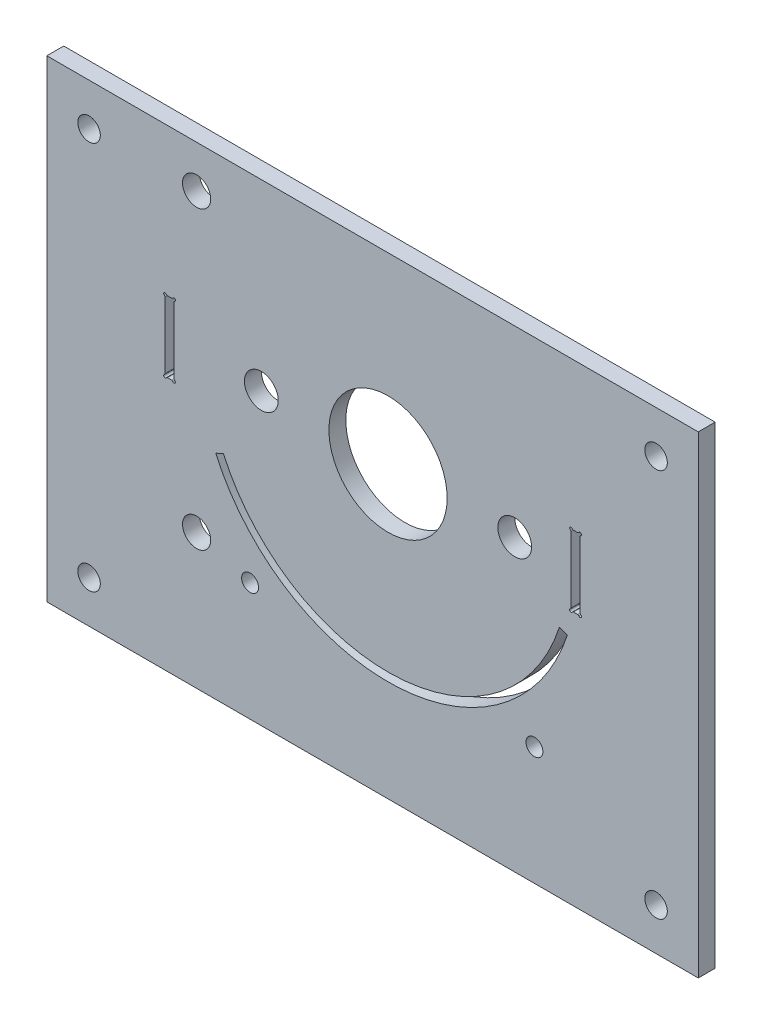
SolidWorks part; units mm, degrees
ref_plane "Front Plane" through (0, 0, 0) normal (0, 0, 1) x (1, 0, 0)
ref_plane "Top Plane" through (0, 0, 0) normal (0, 1, 0) x (1, 0, 0)
ref_plane "Right Plane" through (0, 0, 0) normal (1, 0, 0) x (0, 0, -1)
sketch "Sketch2" plane through (0, 0, 0) normal (0, 0, 1) x (1, 0, 0)
  line L12 (0, 0) -> (0, -103) construction
  line L13 (0, 50) -> (-68, 50) construction
  line L23 (0, 0) -> (0, 50) construction
  line L24 (0, 0) -> (-76, 0) construction
  line L25 (-76, -12.6) -> (-76, 12.6)
  line L26 (-76, 12.6) -> (-79.2, 12.6)
  line L27 (-79.2, 12.6) -> (-79.2, -12.6)
  line L28 (-79.2, -12.6) -> (-76, -12.6)
  line L29 (-68, 50) -> (-68, 65) construction
  line L30 (-79.2, 0) -> (-106.2, 0) construction
  line L31 (-106.2, 0) -> (-106.2, 50) construction
  line L33 (-68, 65) -> (95.2, 65)
  line L41 (0, 0) -> (60, 0) construction
  line L42 (60, 0) -> (65, 0) construction
  line L43 (65, -12.6) -> (65, 12.6)
  line L44 (65, 12.6) -> (68.2, 12.6)
  line L45 (68.2, 12.6) -> (68.2, -12.6)
  line L46 (65, -12.6) -> (68.2, -12.6)
  line L47 (68.2, 0) -> (95.2, 0) construction
  line L48 (95.2, 0) -> (95.2, 50) construction
  line L54 (-68, 50) -> (-68, -55) construction
  line L59 (95.2, 65) -> (110.2, 65)
  line L62 (0, -103) -> (110.2, -103)
  line L63 (110.2, 65) -> (110.2, -103)
  line L64 (-68, 65) -> (-106.2, 65)
  line L65 (-106.2, 65) -> (-121.2, 65)
  line L66 (-121.2, 65) -> (-121.2, -103)
  line L67 (0, -103) -> (-121.2, -103)
  circle A7 centre (0, 0) radius 21
  circle A8 centre (-68, 50) radius 5 construction
  circle A9 centre (-68, -55) radius 5 construction
  point P9 (-76, 0)
  point P13 (0, -103)
  point P25 (65, 0)
  dimension "D1" = 42
  dimension "D4" = 10
  dimension "D10" = 27
  dimension "D11" = 15
  dimension "D12" = 15
  dimension "D26" = 10
  dimension "D2" = 103
  dimension "D3" = 68
  dimension "D5" = 76
  dimension "D6" = 50
  dimension "D7" = 25.2
  dimension "D8" = 3.2
  dimension "D9" = 15
  dimension "D14" = 60
  dimension "D15" = 5
  dimension "D16" = 25.2
  dimension "D17" = 3.2
  dimension "D18" = 27
  dimension "D19" = 50
  dimension "D20" = 50
  dimension "D25" = 105
extrude "Boss-Extrude1" add sketch "Sketch2" along normal mid plane 6
sketch "Sketch6" plane through (0, 0, 0) normal (0, 0, 1) x (1, 0, 0)
  line L0 (-121.2, 65) -> (-106.2, 65) construction
  line L1 (110.2, 65) -> (-121.2, 65) construction
  line L2 (-106.2, 65) -> (-106.2, 50) construction
  line L3 (110.2, 65) -> (95.2, 65) construction
  line L4 (95.2, 65) -> (95.2, 50) construction
  line L5 (110.2, -103) -> (95.2, -103) construction
  line L6 (-121.2, -103) -> (110.2, -103) construction
  line L7 (95.2, -103) -> (95.2, -88) construction
  line L8 (-121.2, -103) -> (-106.2, -103) construction
  line L9 (-106.2, -103) -> (-106.2, -88) construction
  line L10 (-106.2, 50) -> (-68, 50) construction
  line L11 (-121.2, 65) -> (-121.2, -103) construction
  line L12 (-68, 50) -> (-68, -55) construction
  dimension "D1" = 15
  dimension "D2" = 15
  dimension "D3" = 15
  dimension "D4" = 15
  dimension "D5" = 15
  dimension "D6" = 15
  dimension "D7" = 15
  dimension "D8" = 15
  dimension "D9" = 53.2
  dimension "D10" = 105
hole_wizard "Ø10.0 (10) Diameter Hole1" positions "Sketch11" profile "Sketch12" hole size "Ø10.0" standard "AS" end condition through all
sketch "Sketch11" plane through (0, 0, 3) normal (0, 0, 1) x (1, 0, 0)
  point P0 (-68, 50)
  point P3 (-68, -55)
sketch "Sketch12" plane through (-68, 50, 3) normal (1, 0, 0) x (0, -1, 0)
  line L0 (0, 0) -> (0, 6)
  line L1 (0, 6) -> (5, 6)
  line L2 (5, 6) -> (5, 0)
  line L5 (5, 0) -> (0, 0)
  line L11 (0, -6.35) -> (0, 107.95) construction
  dimension "Thru Hole Dia." = 10
  dimension "Thru Hole Depth" = 6
hole_wizard "Ø8.0 (8) Diameter Hole1" positions "Sketch13" profile "Sketch14" hole size "Ø8.0" standard "ANSI Metric" end condition through all
sketch "Sketch13" plane through (0, 0, 3) normal (0, 0, 1) x (1, 0, 0)
  point P0 (-106.2, 50)
  point P3 (-106.2, -88)
  point P6 (95.2, -88)
  point P9 (95.2, 50)
sketch "Sketch14" plane through (-106.2, 50, 3) normal (1, 0, 0) x (0, -1, 0)
  line L0 (0, 0) -> (0, 6)
  line L1 (0, 6) -> (4, 6)
  line L2 (4, 6) -> (4, 0)
  line L5 (4, 0) -> (0, 0)
  line L11 (0, -6.35) -> (0, 107.95) construction
  dimension "Thru Hole Dia." = 8
  dimension "Thru Hole Depth" = 6
sketch "Sketch15" plane through (0, 0, 3) normal (0, 0, 1) x (1, 0, 0)
  line L0 (-45, 0) -> (45, 0) construction
  point P5 (0, 0)
  point P7 (-45, 0)
  point P8 (45, 0)
  dimension "D1" = 90
hole_wizard "Ø12.0 (12) Diameter Hole1" positions "Sketch16" profile "Sketch17" hole size "Ø12.0" standard "AS" end condition through all
sketch "Sketch16" plane through (0, 0, 3) normal (0, 0, 1) x (1, 0, 0)
  point P0 (-45, 0)
  point P3 (45, 0)
sketch "Sketch17" plane through (-45, 0, 3) normal (1, 0, 0) x (0, -1, 0)
  line L0 (0, 0) -> (0, 6)
  line L1 (0, 6) -> (6, 6)
  line L2 (6, 6) -> (6, 0)
  line L5 (6, 0) -> (0, 0)
  line L11 (0, -6.35) -> (0, 107.95) construction
  dimension "Thru Hole Dia." = 12
  dimension "Thru Hole Depth" = 6
sketch "Sketch18" plane through (0, 0, -3) normal (0, 0, -1) x (-1, 0, 0)
  line L0 (0, 0) -> (0, -67) construction
  line L1 (-60.8676, -19.7771) -> (-63.7208, -20.7041)
  line L2 (58.4669, -26.0311) -> (61.2075, -27.2514)
  line L3 (79.2, 12.6) -> (79.2, -12.6) construction
  line L4 (79.2, -12.6) -> (76, -12.6) construction
  line L5 (76, 12.6) -> (79.2, 12.6) construction
  arc A0 (-63.7208, -20.7041) -> (61.2075, -27.2514) centre (0, 0) ccw
  arc A1 (-60.8676, -19.7771) -> (58.4669, -26.0311) centre (0, 0) ccw
  dimension "D1" = 134
  dimension "D2" = 3
  dimension "D6" = 79.2
  dimension "D3" = 72
  dimension "D4" = 66
  dimension "D5" = 17.9925
  dimension "D7" = 142.9208
  dimension "D8" = 12.6
extrude "Cut-Extrude1" cut sketch "Sketch18" against normal through all both and the other way through all
sketch "Sketch19" plane through (0, 0, -3) normal (0, 0, -1) x (-1, 0, 0)
  circle A0 centre (-65, -12.6) radius 0.5
  circle A1 centre (-68.2, -12.6) radius 0.5
  circle A2 centre (-68.2, 12.6) radius 0.5
  circle A3 centre (-65, 12.6) radius 0.5
  circle A4 centre (79.2, -12.6) radius 0.5
  circle A5 centre (76, -12.6) radius 0.5
  circle A6 centre (79.2, 12.6) radius 0.5
  circle A7 centre (76, 12.6) radius 0.5
  dimension "D1" = 1
extrude "Cut-Extrude2" cut sketch "Sketch19" against normal through all
fillet "Fillet1" radius 0.5 16 edges at (-79.2, -12.1, 0) (-78.7, -12.6, 0) (-76.5, -12.6, 0) (-76, -12.1, 0) (-76, 12.1, 0) (-76.5, 12.6, 0) (-78.7, 12.6, 0) (-79.2, 12.1, 0) (65.5, -12.6, 0) (67.7, -12.6, 0) (68.2, -12.1, 0) (65, -12.1, 0) (65, 12.1, 0) (65.5, 12.6, 0) (68.2, 12.1, 0) (67.7, 12.6, 0)
sketch "Sketch20" plane through (0, 0, 3) normal (0, 0, 1) x (1, 0, 0)
  line L0 (0, 0) -> (-49, -61) construction
  line L1 (0, 0) -> (52, -61) construction
  line L2 (0, 0) -> (0, -143.0041) construction
  line L4 (-79.2, 11.734) -> (-79.2, -11.734) construction
  line L5 (67.334, 12.6) -> (65.866, 12.6) construction
  circle A1 centre (0, 0) radius 21 construction
  dimension "D1" = 42
  dimension "D2" = 38.774
  dimension "D3" = 40.446
  dimension "D4" = 61
  dimension "D5" = 61
  dimension "D6" = 79.2
  dimension "D7" = 146.534
  dimension "D8" = 0.866
  dimension "D9" = 12.6
hole_wizard "Ø6.0 (6) Diameter Hole1" positions "Sketch23" profile "Sketch22" hole size "Ø6.0" standard "AS" end condition through all
sketch "Sketch23" plane through (0, 0, 3) normal (0, 0, 1) x (1, 0, 0)
  point P0 (-49, -61)
  point P3 (52, -61)
sketch "Sketch22" plane through (-49, -61, 3) normal (1, 0, 0) x (0, -1, 0)
  line L0 (0, 0) -> (0, 6)
  line L1 (0, 6) -> (3, 6)
  line L2 (3, 6) -> (3, 0)
  line L5 (3, 0) -> (0, 0)
  line L11 (0, -6.35) -> (0, 107.95) construction
  dimension "Thru Hole Dia." = 6
  dimension "Thru Hole Depth" = 6
